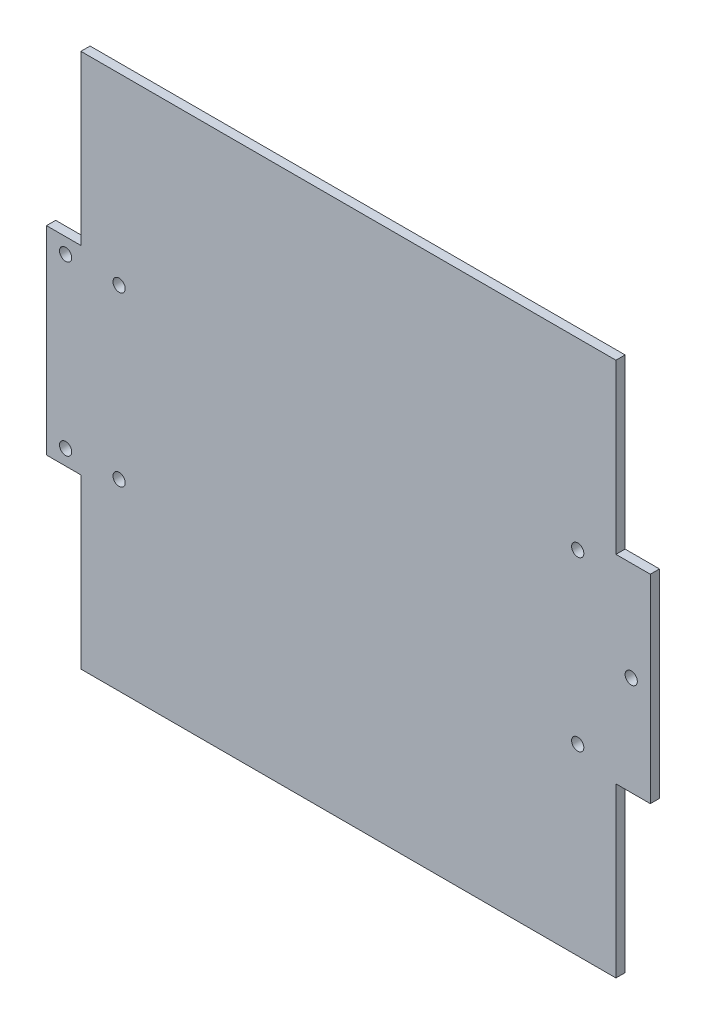
SolidWorks part; units mm, degrees
material "Custom Plastic"
ref_plane "Front Plane" through (0, 0, 0) normal (0, 0, 1) x (1, 0, 0)
ref_plane "Top Plane" through (0, 0, 0) normal (0, 1, 0) x (1, 0, 0)
ref_plane "Right Plane" through (0, 0, 0) normal (1, 0, 0) x (0, 0, -1)
sketch "Sketch1" plane through (0, 0, 0) normal (0, 0, 1) x (1, 0, 0)
  line L0 (138, 70) -> (-2, 70) construction
  line L1 (0, 0) -> (140, 0)
  line L2 (0, 0) -> (0, 44)
  line L3 (0, 140) -> (140, 140)
  line L4 (140, 0) -> (140, 44)
  line L5 (0, 96) -> (-9, 96)
  line L6 (-9, 96) -> (-9, 44)
  line L7 (-9, 44) -> (0, 44)
  line L8 (140, 44) -> (149, 44)
  line L9 (149, 44) -> (149, 96)
  line L10 (149, 96) -> (140, 96)
  line L11 (-2, 70) -> (-9, 70) construction
  line L12 (0, 96) -> (0, 140)
  line L13 (140, 96) -> (140, 140)
  dimension "D2" = 9
  dimension "D3" = 52
  dimension "D1" = 140
  dimension "D5" = 140
extrude "Boss-Extrude1" add sketch "Sketch1" along normal blind 2.4
hole_wizard "Ø3.2 (3.2) Diameter Hole1" positions "Sketch6" profile "Sketch5" hole size "Ø3.2" standard "Ansi Metric"
sketch "Sketch6" plane through (0, 0, 0) normal (0, 0, -1) x (-1, 0, 0)
  line L0 (6.0733, 70) -> (-132.5, 70) construction
  line L5 (-130, 92) -> (-130, 48) construction
  line L9 (-70, 140) -> (-70, 0) construction
  line L10 (-140, 140) -> (0, 140) construction
  line L11 (0, 0) -> (-140, 0) construction
  line L13 (-10, 92) -> (-10, 48) construction
  line L14 (-146.0733, 70) -> (-7.5, 70) construction
  point P20 (-130, 92)
  point P22 (-130, 48)
  point P48 (-10, 92)
  point P50 (-10, 48)
  dimension "D1" = 60
  dimension "D3" = 22
  dimension "D4" = 44
sketch "Sketch5" plane through (130, 92, 0) normal (1, 0, 0) x (0, 1, 0)
  line L0 (0, 0) -> (0, 4.9614)
  line L1 (0, 4.9614) -> (1.6, 4)
  line L2 (1.6, 4) -> (1.6, 0)
  line L5 (1.6, 0) -> (0, 0)
  line L10 (0, 4.9614) -> (-1.6, 4) construction
  line L11 (0, -6.35) -> (0, 107.95) construction
  dimension "Hole Dia." = 3.2
  dimension "Hole Depth" = 4
  dimension "Drill Angle" = 118
sketch "Sketch7" plane through (0, 0, 0) normal (0, 0, -1) x (-1, 0, 0)
  line L0 (-70, 140) -> (-70, 0) construction
  line L1 (-140, 140) -> (0, 140) construction
  line L2 (0, 0) -> (-140, 0) construction
  line L3 (-61.8, 132) -> (-78.2, 132) construction
  circle A0 centre (-78.2, 132) radius 1.5
  circle A1 centre (-61.8, 132) radius 1.5
  dimension "D2" = 3
  dimension "D3" = 8.2
  dimension "D1" = 8.2
  dimension "D4" = 8
extrude "Cut-Extrude1" [suppressed] cut sketch "Sketch7" against normal through all
sketch "Sketch8" plane through (0, 0, 2.4) normal (0, 0, 1) x (1, 0, 0)
  line L1 (10, 92) -> (-4, 92) construction
  line L2 (10, 92) -> (10, 48) construction
  line L3 (10, 48) -> (-4, 48) construction
  line L4 (-4, 92) -> (-4, 48) construction
  line L5 (130, 92) -> (144, 92) construction
  line L6 (130, 92) -> (130, 48) construction
  line L7 (130, 48) -> (144, 48) construction
  line L8 (144, 92) -> (144, 48) construction
  circle A0 centre (-4, 92) radius 1.6
  circle A1 centre (-4, 48) radius 1.6
  circle A2 centre (144, 70) radius 1.6
  dimension "D2" = 3.2
  dimension "D1" = 14
extrude "Cut-Extrude2" cut sketch "Sketch8" against normal through all
